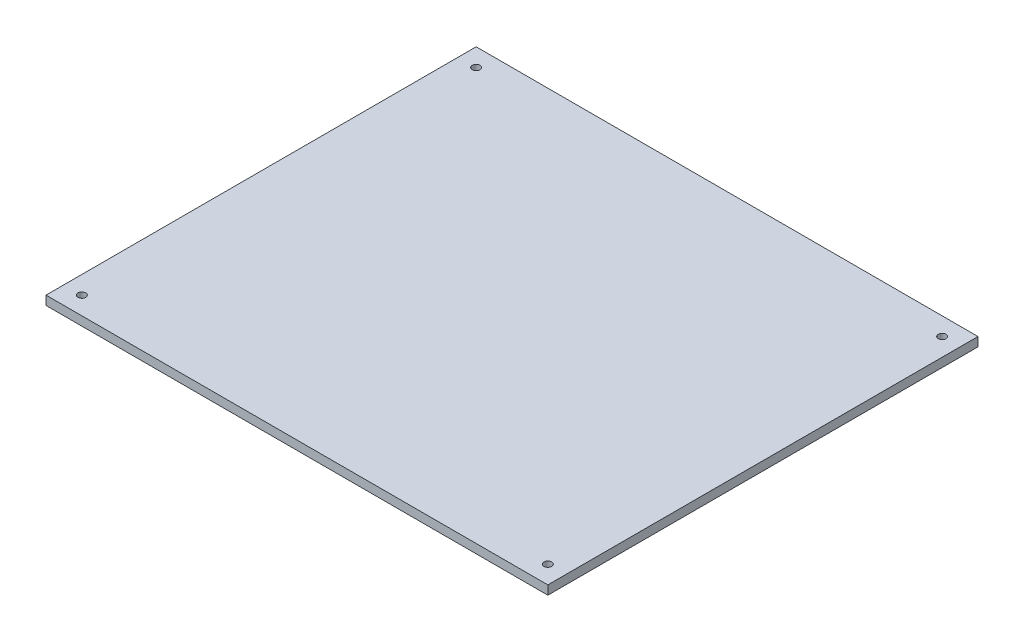
SolidWorks part; units mm, degrees
ref_plane "Front Plane" through (0, 0, 0) normal (0, 0, 1) x (1, 0, 0)
ref_plane "Top Plane" through (0, 0, 0) normal (0, 1, 0) x (1, 0, 0)
ref_plane "Right Plane" through (0, 0, 0) normal (1, 0, 0) x (0, 0, -1)
sketch "Sketch1" plane through (0, 0, 0) normal (0, 1, 0) x (1, 0, 0)
  line L1 (0, 0) -> (177.8, 0)
  line L2 (0, 0) -> (0, 152.4)
  line L3 (0, 152.4) -> (177.8, 152.4)
  line L4 (177.8, 0) -> (177.8, 152.4)
  circle A0 centre (6.35, 146.05) radius 1.375
  circle A2 centre (171.45, 146.05) radius 1.375
  circle A3 centre (6.35, 6.35) radius 1.375
  circle A4 centre (171.45, 6.35) radius 1.375
  dimension "D3" = 2.75
  dimension "D12" = 2.75
  dimension "D1" = 152.4
  dimension "D2" = 177.8
  dimension "D4" = 6.35
  dimension "D5" = 6.35
  dimension "D6" = 6.35
  dimension "D7" = 6.35
  dimension "D8" = 6.35
  dimension "D9" = 6.35
  dimension "D10" = 6.35
  dimension "D11" = 6.35
extrude "Boss-Extrude1" add sketch "Sketch1" along normal blind 3.175
